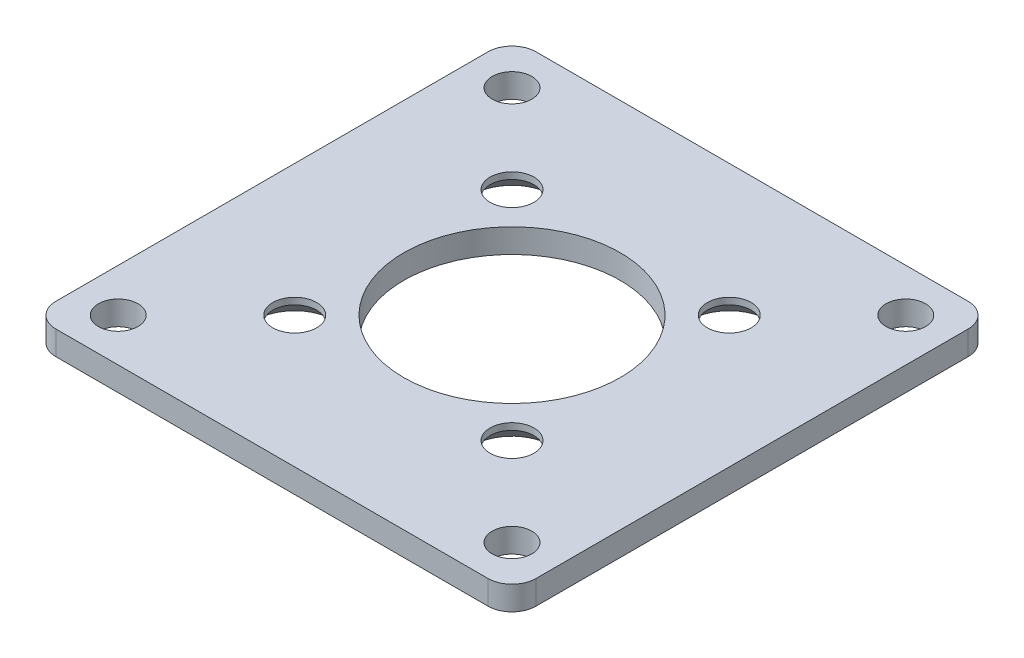
SolidWorks part; units mm, degrees
ref_plane "Front" through (0, 0, 0) normal (0, 0, 1) x (1, 0, 0)
ref_plane "Top" through (0, 0, 0) normal (0, 1, 0) x (1, 0, 0)
ref_plane "Right" through (0, 0, 0) normal (1, 0, 0) x (0, 0, -1)
sketch "Sketch1" plane through (0, 0, 0) normal (0, 1, 0) x (1, 0, 0)
  line L1 (31.75, -31.75) -> (-31.75, -31.75)
  line L2 (31.75, -31.75) -> (31.75, 31.75)
  line L3 (31.75, 31.75) -> (-31.75, 31.75)
  line L4 (-31.75, -31.75) -> (-31.75, 31.75)
  line L5 (31.75, -31.75) -> (-31.75, 31.75) construction
  line L6 (31.75, 31.75) -> (-31.75, -31.75) construction
  point P0 (0, 0)
  dimension "D1" = 63.5
  dimension "D2" = 63.5
extrude "Boss-Extrude1" add sketch "Sketch1" along normal blind 3.175
sketch "Sketch2" plane through (0, 3.175, 0) normal (0, 1, 0) x (1, 0, 0)
  circle A0 centre (0, 0) radius 14.3129
  dimension "D1" = 28.6258
extrude "Cut-Extrude1" cut sketch "Sketch2" against normal up to next
sketch "Sketch3" plane through (0, 0, 0) normal (0, -1, 0) x (1, 0, 0)
  circle A0 centre (-14.3684, 14.3684) radius 2.1 construction
  circle A1 centre (-14.3684, -14.3684) radius 2.1 construction
  circle A2 centre (14.3684, 14.3684) radius 2.1 construction
  circle A3 centre (14.3684, -14.3684) radius 2.1 construction
  circle A4 centre (-14.3684, 14.3684) radius 2.1
  circle A5 centre (-14.3684, -14.3684) radius 2.1
  circle A6 centre (14.3684, 14.3684) radius 2.1
  circle A7 centre (14.3684, -14.3684) radius 2.1
hole_wizard "CSK for M5 Flat Head Machine Screw1" positions "3DSketch1" profile "Sketch4" countersink size "M5" standard "ANSI Metric"
sketch3d "3DSketch1"
  point P0 (-14.3684, 0, 14.3684)
  point P3 (14.3684, 0, 14.3684)
  point P6 (14.3684, 0, -14.3684)
  point P9 (-14.3684, 0, -14.3684)
sketch "Sketch4" plane through (-14.3684, 0, 14.3684) normal (1, 0, 0) x (0, 0, -1)
  line L0 (0, 0) -> (0, 8.0925)
  line L1 (0, 8.0925) -> (2.9, 6.35)
  line L2 (2.9, 6.35) -> (2.9, 2.3)
  line L3 (2.9, 2.3) -> (5.2, 0)
  line L5 (5.2, 0) -> (0, 0)
  line L6 (-2.9, 2.3) -> (-5.2, 0) construction
  line L10 (0, 8.0925) -> (-2.9, 6.35) construction
  line L11 (0, -6.35) -> (0, 107.95) construction
  dimension "Hole Dia." = 5.8
  dimension "Hole Depth" = 6.35
  dimension "Near C'Sink Dia." = 10.4
  dimension "Near C'Sink Angle" = 90
  dimension "Drill Angle" = 118
fillet "Fillet1" radius 3.175 4 edges at (-31.75, 1.5875, 31.75) (31.75, 1.5875, 31.75) (31.75, 1.5875, -31.75) (-31.75, 1.5875, -31.75)
sketch "Sketch5" plane through (0, 0, 0) normal (0, -1, 0) x (-1, 0, 0)
  line L0 (0, 0) -> (-30.8201, -30.8201) construction
  arc A0 (-31.75, -28.575) -> (-28.575, -31.75) centre (-28.575, -28.575) ccw construction
  circle A1 centre (-26.0427, -26.0427) radius 2.6162
  circle A2 centre (-26.0427, 26.0427) radius 2.6162
  circle A3 centre (26.0427, 26.0427) radius 2.6162
  circle A4 centre (26.0427, -26.0427) radius 2.6162
  point P17 (0, 0)
  dimension "D2" = 5.2324
  dimension "D1" = 36.83
  dimension "D3" = 4
extrude "Cut-Extrude2" cut sketch "Sketch5" against normal up to next
